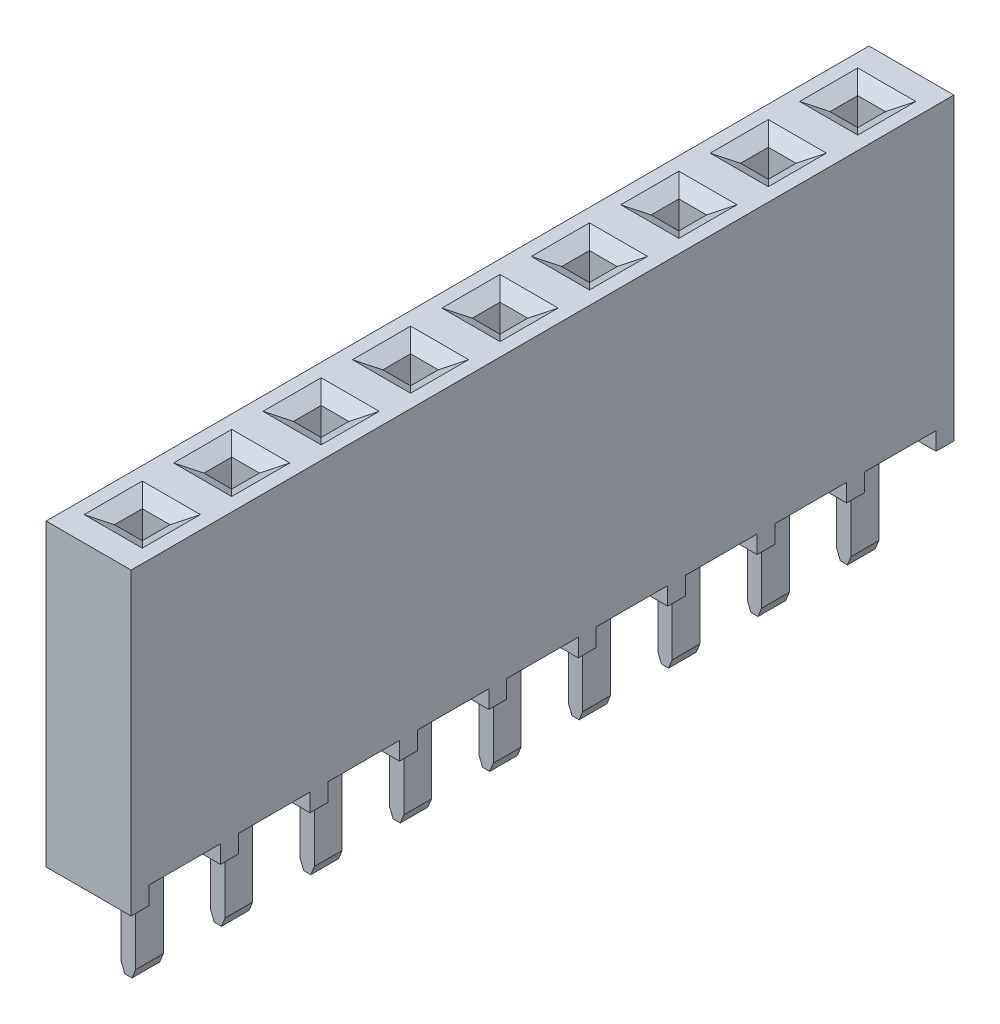
SolidWorks part; units mm, degrees
ref_plane "Front" through (0, 0, 0) normal (0, 0, 1) x (1, 0, 0)
ref_plane "Top" through (0, 0, 0) normal (0, 1, 0) x (1, 0, 0)
ref_plane "Right" through (0, 0, 0) normal (1, 0, 0) x (0, 0, -1)
sketch "Sketch1" plane through (0, 0, 0) normal (0, 1, 0) x (1, 0, 0)
  line L0 (-1.2065, -11.684) -> (1.2065, 11.684) construction
  line L1 (-1.2065, 11.684) -> (1.2065, 11.684)
  line L2 (-1.2065, 11.684) -> (-1.2065, -11.684)
  line L3 (-1.2065, -11.684) -> (1.2065, -11.684)
  line L4 (1.2065, 11.684) -> (1.2065, -11.684)
  dimension "D1" = 23.368
  dimension "D2" = 2.413
extrude "Main Body" add sketch "Sketch1" along normal blind 8.509
ref_plane "Plane1" through (0, 0, -7.62) normal (0, 0, -1) x (-1, 0, 0)
ref_plane "Plane2" through (0, 0, -10.16) normal (0, 0, -1) x (-1, 0, 0)
ref_plane "Plane3" through (0, 0, 0) normal (0, 0, 1) x (1, 0, 0)
ref_plane "Plane4" through (0, 0, -2.54) normal (0, 0, 1) x (1, 0, 0)
sketch "Sketch5" plane through (1.2065, 0, 0) normal (1, 0, 0) x (0, 0, -1)
  line L0 (-11.684, 0) -> (11.684, 0) construction
  line L1 (9.144, 0) -> (11.176, 0)
  line L2 (9.144, 0) -> (9.144, 0.508)
  line L3 (9.144, 0.508) -> (11.176, 0.508)
  line L4 (11.176, 0) -> (11.176, 0.508)
  line L5 (10.16, 0.7418) -> (10.16, -0.7099) construction
  line L6 (11.684, 8.509) -> (11.684, 0) construction
  dimension "D1" = 0.508
  dimension "D2" = 1.524
  dimension "D3" = 0.508
extrude "Cut-Extrude2" cut sketch "Sketch5" against normal up to next
pattern_linear "LPattern1" count 9 spacing 2.54 along (0, 0, 1) of "Cut-Extrude2"
sketch "Sketch2" plane through (0, 8.509, 0) normal (0, 1, 0) x (-1, 0, 0)
  line L0 (0, -0.6833) -> (0, -4.4888) construction
  line L1 (-0.3937, -10.5537) -> (0.3937, -10.5537)
  line L2 (-0.3937, -10.5537) -> (-0.3937, -9.7663)
  line L3 (-0.3937, -9.7663) -> (0.3937, -9.7663)
  line L4 (0.3937, -10.5537) -> (0.3937, -9.7663)
  line L5 (0, 0) -> (-2.54, 0) construction
  line L6 (0.3937, -10.5537) -> (-0.3937, -9.7663) construction
  line L8 (-1.2065, -11.684) -> (1.2065, -11.684) construction
  line L9 (-1.2065, 11.684) -> (-1.2065, -11.684) construction
  point P8 (0, -10.16)
  dimension "D1" = 1.524
  dimension "D2" = 0.7874
  dimension "D3" = 0.7874
  dimension "D4" = 1.2065
extrude "Cut-Extrude1" cut sketch "Sketch2" against normal through all
chamfer "Chamfer1" distance 0.4318 angle 30 4 edges at (0.3937, 8.509, -10.16) (0, 8.509, -10.5537) (-0.3937, 8.509, -10.16) (0, 8.509, -9.7663)
pattern_linear "LPattern2" count 9 spacing 2.54 along (0, 0, 1) of "Chamfer1", "Cut-Extrude1"
sketch "Sketch4" plane through (0, 0, -10.16) normal (0, 0, -1) x (-1, 0, 0)
  line L0 (0, 2.0688) -> (0, -17.6627) construction
  line L1 (0.3937, 0.508) -> (0.3937, 8.2597) construction
  line L2 (-0.3937, 0.508) -> (-0.3937, 8.2597) construction
  line L3 (-0.3937, 1.016) -> (0.3937, 1.016)
  line L5 (-0.2032, 0.889) -> (-0.2032, -2.3876)
  line L6 (-0.1016, -2.6416) -> (0.1016, -2.6416)
  line L7 (0.2032, 0.889) -> (0.2032, -2.3876)
  line L8 (0.1016, -2.6416) -> (0.2032, -2.3876)
  line L9 (-0.2032, -2.3876) -> (-0.1016, -2.6416)
  line L10 (-1.2065, 0) -> (1.2065, 0) construction
  line L11 (0.3937, 1.016) -> (0.3937, 0.889)
  line L12 (0.3937, 0.889) -> (0.2032, 0.889)
  line L13 (-0.2032, 0.889) -> (-0.3937, 0.889)
  line L14 (-0.3937, 0.889) -> (-0.3937, 1.016)
  dimension "D1" = 0.254
  dimension "D2" = 0.2032
  dimension "D3" = 0.4064
  dimension "D4" = 2.6416
  dimension "D5" = 0.7874
  dimension "D6" = 0.889
  dimension "D7" = 1.016
extrude "PIN" add sketch "Sketch4" along normal mid plane 0.7874
pattern_linear "LPattern4" count 9 spacing 2.54 along (0, 0, 1) of "PIN"
sketch "Sketch7" plane through (0, 0, -10.16) normal (0, 0, -1) x (-1, 0, 0)
  line L0 (-0.2032, 1.016) -> (-0.2032, -0.9144)
  line L1 (0.6096, -1.3208) -> (1.4605, -1.3208)
  line L2 (1.4605, -1.3208) -> (1.4605, -1.7272)
  line L3 (1.4605, -1.7272) -> (0.6096, -1.7272)
  line L4 (0.2032, -0.9144) -> (0.2032, 1.016)
  line L5 (-0.2032, 1.016) -> (-0.3937, 1.016)
  line L6 (0, 1.4788) -> (0, -2.2478) construction
  line L10 (1.2065, 8.509) -> (1.2065, 0) construction
  line L11 (-0.3937, 1.016) -> (-0.3937, 1.27)
  line L12 (-0.3937, 1.27) -> (0.3937, 1.27)
  line L13 (0.3937, 1.27) -> (0.3937, 1.016)
  line L14 (0.3937, 1.016) -> (0.2032, 1.016)
  line L16 (1.4605, -1.524) -> (-2.3476, -1.524) construction
  line L17 (-1.2065, 0) -> (1.2065, 0) construction
  line L18 (1.2065, 0.508) -> (-1.2065, 0.508) construction
  arc A0 (-0.2032, -0.9144) -> (0.6096, -1.7272) centre (0.6096, -0.9144) ccw
  arc A1 (0.6096, -1.3208) -> (0.2032, -0.9144) centre (0.6096, -0.9144) cw
  dimension "D9" = 0.8128
  dimension "D10" = 0.4064
  dimension "D1" = 1.2065
  dimension "D2" = 0.4064
  dimension "D3" = 0.4064
  dimension "D4" = 1.524
  dimension "D6" = 0.7874
  dimension "D7" = 0.762
  dimension "D8" = 0.254
  dimension "A" = 0.254
sketch "Sketch8" plane through (0, 0, -7.62) normal (0, 0, -1) x (-1, 0, 0)
  line L0 (0.2032, 1.016) -> (0.2032, -0.9144)
  line L1 (-0.3937, 1.27) -> (0.3937, 1.27)
  line L2 (1.2065, 8.509) -> (1.2065, 0) construction
  line L3 (0.3937, 1.016) -> (0.2032, 1.016)
  line L5 (-0.3937, 1.016) -> (-0.3937, 1.27)
  line L6 (0.3937, 1.016) -> (0.3937, 1.27)
  line L7 (-1.2065, 0) -> (1.2065, 0) construction
  line L8 (-0.2032, 1.016) -> (-0.2032, -0.9144)
  line L9 (0, 1.9479) -> (0, -2.4889) construction
  line L10 (2.9301, -1.524) -> (0.4606, -1.524) construction
  line L11 (1.2065, 8.509) -> (1.2065, 0) construction
  line L13 (-0.2032, 1.016) -> (-0.2032, -3.4544)
  line L15 (0.6096, -1.7272) -> (1.4605, -1.7272)
  line L16 (1.4605, -1.7272) -> (1.4605, -1.3208)
  line L17 (1.4605, -1.3208) -> (0.6096, -1.3208)
  line L18 (0.6096, -4.2672) -> (1.4605, -4.2672)
  line L19 (0.2032, -3.4544) -> (0.2032, 1.016)
  line L20 (1.4605, -3.8608) -> (0.6096, -3.8608)
  line L21 (1.4605, -4.2672) -> (1.4605, -3.8608)
  line L22 (0.3937, 1.27) -> (-0.3937, 1.27)
  line L23 (-0.3937, 1.016) -> (-0.2032, 1.016)
  line L24 (0.2032, 1.016) -> (0.3937, 1.016)
  line L25 (0.3937, 1.016) -> (0.3937, 1.27)
  line L26 (-0.3937, 1.016) -> (-0.3937, 1.27)
  line L27 (0.3937, 0.508) -> (0.3937, 0.889) construction
  line L28 (-0.3937, 0.508) -> (-0.3937, 0.889) construction
  line L29 (0, 1.27) -> (0, -2.4889) construction
  line L30 (1.4605, -4.064) -> (1.27, -4.064) construction
  line L31 (-0.2032, 1.016) -> (-0.3937, 1.016)
  arc A0 (0.6096, -3.8608) -> (0.2032, -3.4544) centre (0.6096, -3.4544) cw
  arc A1 (0.6096, -4.2672) -> (-0.2032, -3.4544) centre (0.6096, -3.4544) cw
  arc A2 (0.6096, -1.7272) -> (-0.2032, -0.9144) centre (0.6096, -0.9144) cw
  arc A3 (0.6096, -1.3208) -> (0.2032, -0.9144) centre (0.6096, -0.9144) cw
  dimension "D5" = 0.8128
  dimension "D6" = 0.4064
  dimension "D14" = 0.4064
  dimension "D15" = 0.8128
  dimension "D1" = 1.27
  dimension "D2" = 0.254
  dimension "D3" = 0.4064
  dimension "D4" = 0.4064
  dimension "D7" = 1.524
  dimension "D8" = 0.4064
  dimension "D9" = 0.254
  dimension "D10" = 2.54
  dimension "D11" = 0.4064
  dimension "D12" = 1.2065
sketch "Sketch9" plane through (0, 0, -7.62) normal (0, 0, -1) x (-1, 0, 0)
  line L0 (0, 1.6049) -> (0, -3.2713) construction
  line L1 (-2.9337, 1.016) -> (-2.9337, 1.27)
  line L2 (0.3937, 1.27) -> (-0.3937, 1.27)
  line L4 (-2.1463, 1.27) -> (-2.9337, 1.27)
  line L5 (0.3937, 1.016) -> (0.3937, 1.27)
  line L6 (-2.3368, 1.016) -> (-2.1463, 1.016)
  line L7 (-0.3937, 1.016) -> (-0.3937, 1.27)
  line L8 (-0.3937, 1.016) -> (-0.2032, 1.016)
  line L10 (0.3937, 1.27) -> (-0.3937, 1.27)
  line L11 (-2.1463, 1.27) -> (-2.1463, 1.016)
  line L12 (-1.9304, -4.2672) -> (1.4605, -4.2672)
  line L13 (1.4605, -4.2672) -> (1.4605, -3.8608)
  line L14 (1.4605, -3.8608) -> (-1.9304, -3.8608)
  line L15 (0.2032, -5.9944) -> (0.2032, 1.016)
  line L16 (-0.3937, 1.016) -> (-0.3937, 1.27)
  line L17 (-0.2032, 1.016) -> (-0.2032, -5.9944)
  line L18 (-0.3937, 1.016) -> (-0.2032, 1.016)
  line L19 (0.2032, 1.016) -> (0.3937, 1.016)
  line L20 (0.3937, 1.27) -> (0.3937, 1.016)
  line L21 (0.2032, -0.9144) -> (0.2032, 1.016)
  line L22 (-0.2032, 1.016) -> (-0.2032, -0.9144)
  line L24 (1.2065, 8.509) -> (1.2065, 0) construction
  line L25 (1.4605, -1.7272) -> (1.4605, -1.3208)
  line L26 (1.4605, -1.3208) -> (0.6096, -1.3208)
  line L27 (-2.3368, -3.4544) -> (-2.3368, 1.016)
  line L29 (-2.7432, 1.016) -> (-2.7432, -3.4544)
  line L31 (-1.2065, 0) -> (1.2065, 0) construction
  line L32 (0.6096, -1.7272) -> (1.4605, -1.7272)
  line L34 (6.2865, -1.524) -> (4.283, -1.524) construction
  line L35 (6.2865, -4.064) -> (4.7316, -4.064) construction
  line L40 (-2.7432, 1.016) -> (-2.9337, 1.016)
  line L41 (-2.54, 1.27) -> (-2.54, -1.7272) construction
  line L42 (0.2032, 1.016) -> (0.3937, 1.016)
  line L43 (0.3937, 0.508) -> (0.3937, 0.889) construction
  line L44 (-0.3937, 0.508) -> (-0.3937, 0.889) construction
  line L45 (0, 1.27) -> (0, -1.198) construction
  line L46 (0.6096, -6.4008) -> (1.4605, -6.4008)
  line L47 (1.4605, -6.4008) -> (1.4605, -6.8072)
  line L48 (1.4605, -6.8072) -> (0.6096, -6.8072)
  line L49 (6.1112, -6.604) -> (4.5563, -6.604) construction
  arc A0 (0.2032, -0.9144) -> (0.6096, -1.3208) centre (0.6096, -0.9144) ccw
  arc A1 (-0.2032, -0.9144) -> (0.6096, -1.7272) centre (0.6096, -0.9144) ccw
  arc A2 (-1.9304, -4.2672) -> (-2.7432, -3.4544) centre (-1.9304, -3.4544) cw
  arc A3 (-1.9304, -3.8608) -> (-2.3368, -3.4544) centre (-1.9304, -3.4544) cw
  arc A4 (0.6096, -6.4008) -> (0.2032, -5.9944) centre (0.6096, -5.9944) cw
  arc A5 (0.6096, -6.8072) -> (-0.2032, -5.9944) centre (0.6096, -5.9944) cw
  dimension "D7" = 1.27
  dimension "D8" = 0.254
  dimension "D11" = 0.4064
  dimension "D12" = 0.8128
  dimension "D4" = 0.4064
  dimension "D5" = 0.8128
  dimension "D15" = 0.4064
  dimension "D16" = 0.8128
  dimension "D2" = 1.524
  dimension "D3" = 0.4064
  dimension "D6" = 0.4064
  dimension "D9" = 1.2065
  dimension "D10" = 2.54
  dimension "D13" = 0.4064
  dimension "D14" = 5.08
  dimension "D17" = 0.4064
  dimension "D18" = 2.54
  dimension "D19" = 0.7874
  dimension "D20" = 0.7874
  dimension "A" = 0.254
sketch "Sketch10" plane through (0, 0, -7.62) normal (0, 0, -1) x (-1, 0, 0)
  line L0 (-2.54, -14.478) -> (-2.54, 0.635)
  line L2 (-0.508, -16.51) -> (-0.2286, -16.51)
  line L3 (-1.2065, 0) -> (1.2065, 0) construction
  line L4 (1.2065, 8.509) -> (1.2065, 0) construction
  arc A0 (-2.54, -14.478) -> (-0.508, -16.51) centre (-0.508, -14.478) ccw
  dimension "D1" = 2.032
  dimension "D5" = 0.635
  dimension "D2" = 16.51
  dimension "D3" = 0.2794
  dimension "D4" = 3.7465
sketch "Sketch6" plane through (0, 0.508, 0) normal (0, 1, 0) x (-1, 0, 0)
  line L0 (-1.2065, -11.684) -> (1.2065, -11.684) construction
  line L3 (-1.7145, -10.9855) -> (-3.3655, -10.9855)
  line L6 (-3.3655, -10.9855) -> (-3.3655, -9.3345)
  line L8 (-3.3655, -9.3345) -> (-1.7145, -9.3345)
  line L10 (-1.7145, -9.3345) -> (-1.7145, -10.9855)
  line L11 (-3.3655, -10.16) -> (-1.7145, -10.16) construction
  line L12 (-2.54, -10.9855) -> (-2.54, -9.3345) construction
  line L14 (1.2065, -11.684) -> (1.2065, 11.684) construction
  dimension "D1" = 1.651
  dimension "D2" = 3.7465
  dimension "D3" = 1.524
sketch "Sketch11" plane through (0, 0, -7.62) normal (0, 0, -1) x (-1, 0, 0)
  line L0 (-0.2032, 1.016) -> (-0.2032, -0.4572)
  line L1 (-2.5781, -1.27) -> (-0.6096, -1.27)
  line L2 (-0.6096, -0.8636) -> (-2.5781, -0.8636)
  line L3 (-2.5781, -0.8636) -> (-2.5781, -1.27)
  line L4 (0.2032, -0.4572) -> (0.2032, 1.016)
  line L5 (0.3937, 1.27) -> (0.3937, 1.016)
  line L6 (0.3937, 1.016) -> (0.2032, 1.016)
  line L7 (0.3937, 1.27) -> (-0.3937, 1.27)
  line L8 (-0.3937, 1.27) -> (-0.3937, 1.016)
  line L9 (-0.3937, 1.016) -> (-0.2032, 1.016)
  line L10 (-0.3937, 0.508) -> (-0.3937, 0.889) construction
  line L11 (-1.2065, 8.509) -> (-1.2065, 0) construction
  line L12 (0, 1.27) -> (0, -1.1346) construction
  line L13 (-1.2065, 0) -> (1.2065, 0) construction
  arc A0 (-0.2032, -0.4572) -> (-0.6096, -0.8636) centre (-0.6096, -0.4572) cw
  arc A1 (-0.6096, -1.27) -> (0.2032, -0.4572) centre (-0.6096, -0.4572) ccw
  dimension "D7" = 1.27
  dimension "D4" = 0.4064
  dimension "D5" = 0.8128
  dimension "D1" = 0.4064
  dimension "D2" = 1.2065
  dimension "D3" = 1.27
  dimension "D6" = 0.4064
sketch "Sketch12" plane through (0, 0, -10.16) normal (0, 0, -1) x (-1, 0, 0)
  line L1 (0.3937, 1.27) -> (-0.3937, 1.27)
  line L3 (-0.3937, 1.016) -> (-0.2032, 1.016)
  line L5 (0.3937, 1.016) -> (0.3937, 1.27)
  line L6 (0, 1.27) -> (0, -2.7927) construction
  line L7 (2.5781, -0.8636) -> (2.5781, -1.27)
  line L8 (2.5781, -1.27) -> (0.6096, -1.27)
  line L9 (0.6096, -0.8636) -> (2.5781, -0.8636)
  line L10 (0.2032, 1.016) -> (0.3937, 1.016)
  line L11 (1.2065, 8.509) -> (1.2065, 0) construction
  line L12 (0.2032, -0.4572) -> (0.2032, 1.016)
  line L13 (-1.2065, 0) -> (1.2065, 0) construction
  line L14 (-0.2032, 1.016) -> (-0.2032, -0.4572)
  line L19 (-0.3937, 1.016) -> (-0.3937, 1.27)
  arc A0 (0.6096, -0.8636) -> (0.2032, -0.4572) centre (0.6096, -0.4572) cw
  arc A1 (0.6096, -1.27) -> (-0.2032, -0.4572) centre (0.6096, -0.4572) cw
  dimension "D7" = 1.27
  dimension "D11" = 0.8128
  dimension "D3" = 1.2065
  dimension "D4" = 0.7874
  dimension "D5" = 1.27
  dimension "D6" = 0.254
  dimension "D8" = 0.4064
  dimension "D10" = 0.4064
sketch "Sketch19" plane through (0, 0, 0) normal (0, 0, 1) x (1, 0, 0)
  line L0 (-3.1115, -1.7272) -> (-3.0603, -1.7272)
  line L1 (-1.3847, -1.7272) -> (-1.3335, -1.7272)
  line L2 (-1.3335, -1.7272) -> (-1.3335, -1.3208)
  line L3 (-1.3335, -1.3208) -> (-3.1115, -1.3208)
  line L4 (-3.1115, -1.3208) -> (-3.1115, -1.7272)
  line L6 (-3.1115, -1.9304) -> (-0.9396, -1.9304) construction
  line L7 (-3.1115, -1.524) -> (-1.3335, -1.524) construction
  line L8 (8.4718, 0) -> (-8.4718, 0) construction
  line L9 (-1.2065, 8.509) -> (-1.2065, 0) construction
  line L10 (-2.2225, -0.508) -> (-2.2225, -1.524) construction
  arc A0 (-2.8741, -1.7724) -> (-3.0603, -1.7272) centre (-3.0603, -2.1336) ccw
  arc A1 (-2.8741, -1.7724) -> (-1.5709, -1.7724) centre (-2.2225, -0.508) ccw
  arc A2 (-1.3847, -1.7272) -> (-1.5709, -1.7724) centre (-1.3847, -2.1336) ccw
  dimension "D1" = 1.4224
  dimension "D6" = 0.4064
  dimension "D2" = 1.524
  dimension "D3" = 0.4064
  dimension "D4" = 0.2032
  dimension "D5" = 1.016
  dimension "D7" = 1.778
sketch "Sketch20" plane through (0, 0, 0) normal (0, 0, 1) x (1, 0, 0)
  line L0 (-2.5334, -1.524) -> (-1.2951, -1.524) construction
  line L1 (-1.2065, 8.509) -> (-1.2065, 0) construction
  line L4 (-3.0603, -1.3208) -> (-3.1115, -1.3208)
  line L5 (-3.1115, -1.3208) -> (-3.1115, -1.0668)
  line L6 (-3.1115, -1.0668) -> (-1.3335, -1.0668)
  line L7 (-1.3847, -1.3208) -> (-1.3335, -1.3208)
  line L8 (-1.3335, -1.3208) -> (-1.3335, -1.0668)
  line L9 (-2.2225, -1.524) -> (-2.2225, -0.6068) construction
  line L10 (-1.2065, 0) -> (1.2065, 0) construction
  arc A0 (-2.8741, -1.366) -> (-1.5709, -1.366) centre (-2.2225, -0.1016) ccw
  arc A1 (-2.8741, -1.366) -> (-3.0603, -1.3208) centre (-3.0603, -1.7272) ccw
  arc A2 (-1.5709, -1.366) -> (-1.3847, -1.3208) centre (-1.3847, -1.7272) cw
  dimension "D1" = 2.8448
  dimension "D4" = 0.4064
  dimension "D2" = 1.016
  dimension "D3" = 1.524
  dimension "D5" = 0.254
  dimension "D6" = 0.4064
  dimension "D7" = 1.778
sketch "Sketch45" plane through (0, 0, -2.54) normal (0, 0, 1) x (1, 0, 0)
  line L0 (-3.1115, -1.3208) -> (-3.048, -1.3208)
  line L1 (-1.3335, -1.3208) -> (-3.1115, -1.3208) construction
  line L2 (-2.931, -1.3036) -> (-2.398, -1.1434)
  line L3 (-2.047, -1.1434) -> (-1.514, -1.3036)
  line L4 (-1.397, -1.3208) -> (-1.3335, -1.3208)
  line L5 (-1.3335, -1.3208) -> (-1.3335, -1.7272)
  line L6 (-1.3335, -1.7272) -> (-3.1115, -1.7272)
  line L7 (-3.1115, -1.7272) -> (-3.1115, -1.3208)
  arc A0 (-3.048, -1.3208) -> (-2.931, -1.3036) centre (-3.048, -0.9144) ccw
  arc A1 (-2.398, -1.1434) -> (-2.047, -1.1434) centre (-2.2225, -1.7272) cw
  arc A2 (-1.514, -1.3036) -> (-1.397, -1.3208) centre (-1.397, -0.9144) ccw
  dimension "D1" = 0.2032
  dimension "D2" = 0.0635
  dimension "D3" = 0.4064
  dimension "D4" = 0.6096
sketch "Sketch46" plane through (0, 0, -2.54) normal (0, 0, 1) x (1, 0, 0)
  line L1 (-1.3847, -1.3208) -> (-1.3335, -1.3208) construction
  line L3 (-3.1115, -1.3208) -> (-3.1115, -1.0668) construction
  line L4 (-3.1115, -1.0668) -> (-1.3335, -1.0668) construction
  line L5 (-1.3335, -1.3208) -> (-1.3335, -1.0668) construction
  line L6 (-3.0603, -1.3208) -> (-3.1115, -1.3208) construction
  line L10 (-1.2951, -1.524) -> (-3.1115, -1.524) construction
  line L11 (-3.1115, -1.9812) -> (-1.3335, -1.9812)
  line L12 (-3.1115, -1.7272) -> (-3.1115, -1.9812)
  line L13 (-3.0603, -1.7272) -> (-3.1115, -1.7272)
  line L14 (-1.3847, -1.7272) -> (-1.3335, -1.7272)
  line L15 (-1.3335, -1.7272) -> (-1.3335, -1.9812)
  arc A0 (-2.8741, -1.366) -> (-1.5709, -1.366) centre (-2.2225, -0.1016) ccw construction
  arc A3 (-2.8741, -1.366) -> (-3.0603, -1.3208) centre (-3.0603, -1.7272) ccw construction
  arc A6 (-2.8741, -1.682) -> (-3.0603, -1.7272) centre (-3.0603, -1.3208) cw
  arc A7 (-1.3847, -1.7272) -> (-1.5709, -1.682) centre (-1.3847, -1.3208) cw
  arc A8 (-2.8741, -1.682) -> (-1.5709, -1.682) centre (-2.2225, -2.9464) cw
sketch "Sketch27" plane through (0, 0, 0) normal (0, 0, 1) x (1, 0, 0)
  line L0 (-3.8171, -6.1976) -> (-2.3191, -6.1976) construction
  line L3 (-2.2225, -7.62) -> (-2.2225, -2.6186) construction
  line L4 (-1.2065, 8.509) -> (-1.2065, 0) construction
  line L5 (-3.0603, -6.4008) -> (-3.1115, -6.4008)
  line L6 (-3.1115, -6.4008) -> (-3.1115, -6.8072)
  line L7 (-3.1115, -6.8072) -> (-1.3335, -6.8072)
  line L8 (-1.3335, -6.8072) -> (-1.3335, -6.4008)
  line L9 (-1.3335, -6.4008) -> (-1.3847, -6.4008)
  line L10 (-3.1115, -6.604) -> (-1.3335, -6.604) construction
  line L11 (-1.2065, 0) -> (1.2065, 0) construction
  arc A0 (-1.5709, -6.3556) -> (-2.8741, -6.3556) centre (-2.2225, -7.62) ccw
  arc A1 (-1.3847, -6.4008) -> (-1.5709, -6.3556) centre (-1.3847, -5.9944) cw
  arc A2 (-3.0603, -6.4008) -> (-2.8741, -6.3556) centre (-3.0603, -5.9944) ccw
  dimension "D1" = 2.8448
  dimension "D7" = 0.4064
  dimension "D2" = 0.4064
  dimension "D3" = 1.016
  dimension "D5" = 0.4064
  dimension "D6" = 1.778
sketch "Sketch28" plane through (0, 0, 0) normal (0, 0, 1) x (1, 0, 0)
  line L0 (-4.004, -6.604) -> (-2.6238, -6.604) construction
  line L3 (-2.2225, -8.0264) -> (-2.2225, -2.6456) construction
  line L4 (-1.2065, 8.509) -> (-1.2065, 0) construction
  line L5 (-1.2065, 0) -> (1.2065, 0) construction
  line L6 (-3.0603, -6.8072) -> (-3.1115, -6.8072)
  line L7 (-3.1115, -6.8072) -> (-3.1115, -7.0612)
  line L8 (-3.1115, -7.0612) -> (-1.3335, -7.0612)
  line L9 (-1.3335, -7.0612) -> (-1.3335, -6.8072)
  line L10 (-1.3335, -6.8072) -> (-1.3847, -6.8072)
  arc A0 (-1.5709, -6.762) -> (-2.8741, -6.762) centre (-2.2225, -8.0264) ccw
  arc A1 (-1.3847, -6.8072) -> (-1.5709, -6.762) centre (-1.3847, -6.4008) cw
  arc A2 (-3.0603, -6.8072) -> (-2.8741, -6.762) centre (-3.0603, -6.4008) ccw
  dimension "D1" = 2.8448
  dimension "D7" = 0.4064
  dimension "D3" = 1.016
  dimension "D4" = 0.2032
  dimension "D5" = 0.254
  dimension "D6" = 1.778
sketch "Sketch38" plane through (0, 0, -2.54) normal (0, 0, 1) x (1, 0, 0)
  line L0 (-1.016, -1.016) -> (2.1645, -1.016) construction
  line L1 (0, -1.905) -> (0, -0.127) construction
  line L2 (0.4064, -0.4657) -> (0.4064, -2.0349) construction
  line L5 (0.2032, -0.1782) -> (0.2032, -0.127)
  line L6 (0.2032, -0.127) -> (-0.2032, -0.127)
  line L7 (-0.2032, -0.127) -> (-0.2032, -1.905)
  line L8 (-1.2065, 0) -> (1.2065, 0) construction
  line L9 (-0.2032, -1.905) -> (0.2032, -1.905)
  line L10 (0.2032, -1.905) -> (0.2032, -1.8538)
  line L12 (-1.2065, 8.509) -> (-1.2065, 0) construction
  arc A0 (0.2032, -0.1782) -> (0.2484, -0.3644) centre (0.6096, -0.1782) ccw
  arc A1 (0.2484, -1.6676) -> (0.2484, -0.3644) centre (-1.016, -1.016) ccw
  arc A2 (0.2032, -1.8538) -> (0.2484, -1.6676) centre (0.6096, -1.8538) cw
  dimension "D1" = 1.4224
  dimension "D5" = 0.4064
  dimension "D4" = 1.778
  dimension "D6" = 0.4064
  dimension "D2" = 1.2065
  dimension "D3" = 1.016
  dimension "D7" = 0.4064
sketch "Sketch39" plane through (0, 0, -2.54) normal (0, 0, 1) x (1, 0, 0)
  line L0 (-1.4224, -1.016) -> (1.423, -1.016) construction
  line L1 (0, -1.016) -> (0, -2.3641) construction
  line L2 (-1.2065, 8.509) -> (-1.2065, 0) construction
  line L3 (-1.2065, 0) -> (1.2065, 0) construction
  line L4 (-0.2032, -0.2834) -> (-0.2032, -0.127)
  line L5 (-0.2032, -0.127) -> (-0.4572, -0.127)
  line L6 (-0.4572, -0.127) -> (-0.4572, -1.905)
  line L7 (-0.4572, -1.905) -> (-0.2032, -1.905)
  line L8 (-0.2032, -1.905) -> (-0.2032, -1.7486)
  arc A0 (-0.2032, -1.7486) -> (-0.2032, -0.2834) centre (-1.4224, -1.016) ccw
  dimension "D1" = 2.8448
  dimension "D2" = 1.016
  dimension "D3" = 0.1564
  dimension "D4" = 0.254
  dimension "D5" = 1.778
  dimension "D6" = 1.2065
sketch "Sketch40" plane through (0, 8.509, 0) normal (0, 1, 0) x (-1, 0, 0)
  circle A0 centre (0, 0) radius 1.7526
  dimension "D1" = 3.5052
sketch "Sketch41" plane through (0, 0, 0) normal (0, 0, 1) x (1, 0, 0)
  line L0 (0, 0) -> (0, 12.0579) construction
  line L1 (-2.8283, 4.7606) -> (-2.8141, 4.7868)
  line L2 (-2.6496, 5.6392) -> (-2.9701, 8.4292)
  line L3 (-2.7178, 8.7122) -> (2.7178, 8.7122)
  line L4 (-2.9718, 10.4747) -> (-2.9718, 5.0805) construction
  line L7 (-2.7178, 8.509) -> (2.7178, 8.509)
  line L8 (-2.4477, 5.6624) -> (-2.7683, 8.4524)
  line L9 (2.8283, 4.7606) -> (2.6354, 4.6902)
  line L10 (-2.8283, 4.7606) -> (-2.6354, 4.6902)
  line L11 (2.4477, 5.6624) -> (2.7683, 8.4524)
  line L12 (2.6496, 5.6392) -> (2.9701, 8.4292)
  line L13 (2.8283, 4.7606) -> (2.8141, 4.7868)
  line L14 (-1.2065, 0) -> (1.2065, 0) construction
  arc A0 (-2.9701, 8.4292) -> (-2.7178, 8.7122) centre (-2.7178, 8.4582) cw
  arc A1 (-2.8141, 4.7868) -> (-2.6496, 5.6392) centre (-4.0849, 5.4742) ccw
  arc A2 (-2.7683, 8.4524) -> (-2.7178, 8.509) centre (-2.7178, 8.4582) cw
  arc A3 (-2.6354, 4.6902) -> (-2.4477, 5.6624) centre (-4.0849, 5.4742) ccw
  arc A4 (2.6354, 4.6902) -> (2.4477, 5.6624) centre (4.0849, 5.4742) cw
  arc A5 (2.7683, 8.4524) -> (2.7178, 8.509) centre (2.7178, 8.4582) ccw
  arc A6 (2.8141, 4.7868) -> (2.6496, 5.6392) centre (4.0849, 5.4742) cw
  arc A7 (2.9701, 8.4292) -> (2.7178, 8.7122) centre (2.7178, 8.4582) ccw
  point P6 (0, 8.7122)
  point P31 (0, 8.509)
  dimension "D1" = 0.254
  dimension "D4" = 0.2032
  dimension "D6" = 1.4448
  dimension "D2" = 8.7122
  dimension "D3" = 2.9718
  dimension "D5" = 3.9516
  dimension "D7" = 2.79
  dimension "D8" = 0.3206
  dimension "D9" = 4.022
sketch "Sketch43" plane through (0, 8.509, 0) normal (0, 1, 0) x (-1, 0, 0)
  line L0 (2.4765, 0) -> (-2.4765, 0) construction
  line L1 (2.4765, -5.0165) -> (-2.4765, -5.0165)
  line L2 (2.4765, -5.0165) -> (2.4765, 5.0165)
  line L3 (2.4765, 5.0165) -> (-2.4765, 5.0165)
  line L4 (-2.4765, -5.0165) -> (-2.4765, 5.0165)
  dimension "D1" = 10.033
  dimension "D2" = 4.953
sketch "Polarize sketch" plane through (0, 8.509, 0) normal (0, 1, 0) x (-1, 0, 0)
  line L0 (-0.8915, -12.5705) -> (0.8865, -10.7925) construction
  line L1 (-0.8915, -12.5705) -> (0.8865, -12.5705)
  line L2 (-0.8915, -12.5705) -> (-0.8915, -10.7925)
  line L3 (-0.8915, -10.7925) -> (0.8865, -10.7925)
  line L4 (0.8865, -12.5705) -> (0.8865, -10.7925)
  line L5 (0.8865, -12.5705) -> (-0.0025, -11.6815) construction
  line L6 (0, -7.5404) -> (0, -10.8194) construction
  line L7 (-1.2065, -11.684) -> (1.2065, -11.684) construction
  line L11 (1.2065, -11.684) -> (1.2065, 11.684) construction
  dimension "D1" = 1.2065
  dimension "D2" = 1.778
  dimension "Width" = 0.0025
  dimension "Height" = 0.0025
sketch "Sketch44" plane through (0, 0, -11.684) normal (0, 0, -1) x (-1, 0, 0)
  line L0 (-1.2065, 5.4864) -> (-0.8255, 4.9784)
  line L1 (-1.2065, 8.509) -> (-1.2065, 0) construction
  line L2 (-0.8255, 4.2164) -> (-1.2065, 3.7084)
  line L3 (-1.2065, 3.7084) -> (-1.2065, 5.4864)
  line L4 (-1.3335, 4.5974) -> (-1.2065, 4.5974) construction
  line L5 (-1.2065, 8.509) -> (1.2065, 8.509) construction
  arc A0 (-0.8255, 4.9784) -> (-0.8255, 4.2164) centre (-1.3335, 4.5974) cw
  dimension "D3" = 0.508
  dimension "D4" = 0.635
  dimension "D1" = 1.778
  dimension "D2" = 3.9116
